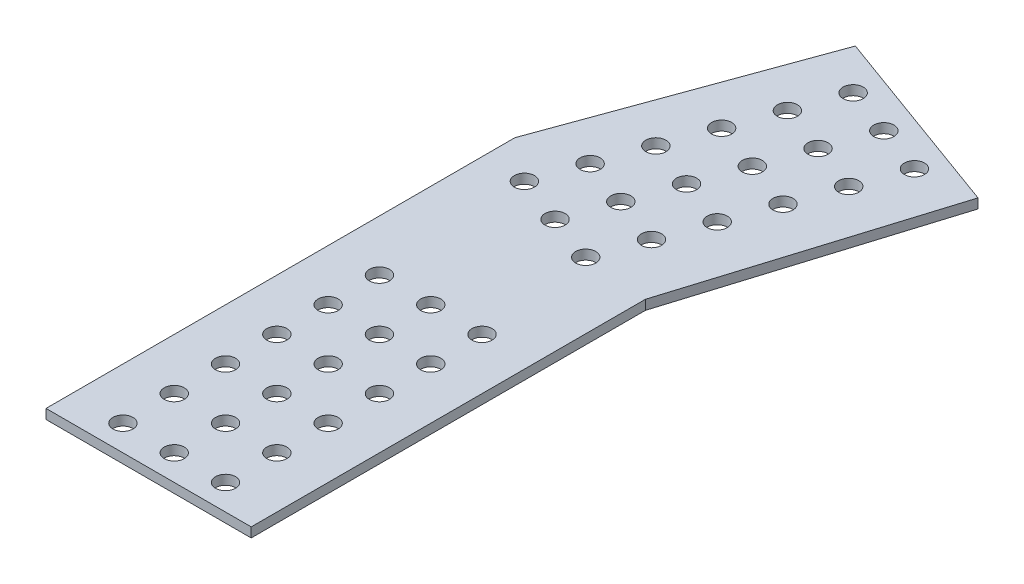
SolidWorks part; units mm, degrees
ref_plane "Front Plane" through (0, 0, 0) normal (0, 0, 1) x (1, 0, 0)
ref_plane "Top Plane" through (0, 0, 0) normal (0, 1, 0) x (1, 0, 0)
ref_plane "Right Plane" through (0, 0, 0) normal (1, 0, 0) x (0, 0, -1)
sketch "Sketch1" plane through (0, 0, 0) normal (0, 1, 0) x (1, 0, 0)
  line L0 (-80.3795, -295.1056) -> (-128.1159, -277.731) construction
  line L1 (-80.3795, -295.1056) -> (128.1159, 277.731) construction
  line L2 (-124.5455, -267.9214) -> (80.3795, 295.1056) construction
  line L3 (128.1159, 277.731) -> (80.3795, 295.1056) construction
  line L4 (-80.3795, -295.1056) -> (80.3795, 295.1056) construction
  line L5 (-128.1159, -277.731) -> (128.1159, 277.731) construction
  line L6 (104.2477, 286.4183) -> (-104.2477, -286.4183) construction
  line L7 (-73.7455, -307.8056) -> (-124.5455, -307.8056)
  line L8 (-73.7455, -307.8056) -> (-73.7455, -422.1056) construction
  line L9 (-73.7455, -422.1056) -> (-124.5455, -422.1056) construction
  line L10 (-124.5455, -307.8056) -> (-124.5455, -422.1056) construction
  line L11 (-99.1455, -307.8056) -> (-99.1455, -422.1056) construction
  line L12 (-105.4955, -307.8056) -> (-105.4955, -422.1056) construction
  line L13 (-99.1455, -307.8056) -> (-99.1455, -288.2754) construction
  line L14 (98.2807, 288.5901) -> (-110.2148, -284.2465) construction
  line L15 (-102.054, -206.1264) -> (-54.3176, -223.501)
  line L16 (-102.054, -206.1264) -> (-124.5455, -267.9214)
  line L19 (-73.7455, -384.0056) -> (-124.5455, -384.0056)
  line L20 (-73.7455, -307.8056) -> (-73.7455, -384.0056)
  line L21 (-124.5455, -307.8056) -> (-124.5455, -384.0056)
  line L22 (-124.5455, -307.8056) -> (-124.5455, -267.9214)
  line L23 (-124.5455, -267.9214) -> (-73.7455, -286.4111)
  line L24 (-73.7455, -307.8056) -> (-73.7455, -286.4111)
  line L25 (-73.7455, -286.4111) -> (-54.3176, -223.501)
  circle A0 centre (-111.8455, -314.1556) radius 2.4892
  circle A1 centre (-111.8455, -326.8556) radius 2.4892
  circle A2 centre (-111.8455, -339.5556) radius 2.4892
  circle A3 centre (-111.8455, -352.2556) radius 2.4892
  circle A4 centre (-111.8455, -364.9556) radius 2.4892
  circle A5 centre (-111.8455, -377.6556) radius 2.4892
  circle A6 centre (-111.8455, -390.3556) radius 2.4892 construction
  circle A7 centre (-111.8455, -403.0556) radius 2.4892 construction
  circle A8 centre (-111.8455, -415.7556) radius 2.4892 construction
  circle A9 centre (-99.1455, -403.0556) radius 2.4892 construction
  circle A10 centre (-99.1455, -390.3556) radius 2.4892 construction
  circle A11 centre (-99.1455, -377.6556) radius 2.4892
  circle A12 centre (-99.1455, -364.9556) radius 2.4892
  circle A13 centre (-99.1455, -352.2556) radius 2.4892
  circle A14 centre (-99.1455, -339.5556) radius 2.4892
  circle A15 centre (-99.1455, -326.8556) radius 2.4892
  circle A16 centre (-99.1455, -314.1556) radius 2.4892
  circle A17 centre (-86.4455, -415.7556) radius 2.4892 construction
  circle A18 centre (-86.4455, -403.0556) radius 2.4892 construction
  circle A19 centre (-86.4455, -390.3556) radius 2.4892 construction
  circle A20 centre (-86.4455, -377.6556) radius 2.4892
  circle A21 centre (-86.4455, -364.9556) radius 2.4892
  circle A22 centre (-86.4455, -352.2556) radius 2.4892
  circle A23 centre (-86.4455, -339.5556) radius 2.4892
  circle A24 centre (-86.4455, -326.8556) radius 2.4892
  circle A25 centre (-86.4455, -314.1556) radius 2.4892
  circle A26 centre (-99.1455, -415.7556) radius 2.4892 construction
  circle A27 centre (90.1418, 284.7949) radius 2.4892 construction
  circle A28 centre (85.7982, 272.8608) radius 2.4892 construction
  circle A29 centre (81.4545, 260.9267) radius 2.4892 construction
  circle A30 centre (77.1108, 248.9926) radius 2.4892 construction
  circle A31 centre (72.7672, 237.0585) radius 2.4892 construction
  circle A32 centre (68.4235, 225.1244) radius 2.4892 construction
  circle A33 centre (64.0799, 213.1903) radius 2.4892 construction
  circle A34 centre (59.7362, 201.2562) radius 2.4892 construction
  circle A35 centre (55.3926, 189.3221) radius 2.4892 construction
  circle A36 centre (51.0489, 177.3881) radius 2.4892 construction
  circle A37 centre (46.7053, 165.454) radius 2.4892 construction
  circle A38 centre (42.3616, 153.5199) radius 2.4892 construction
  circle A39 centre (38.0179, 141.5858) radius 2.4892 construction
  circle A40 centre (33.6743, 129.6517) radius 2.4892 construction
  circle A41 centre (29.3306, 117.7176) radius 2.4892 construction
  circle A42 centre (24.987, 105.7835) radius 2.4892 construction
  circle A43 centre (20.6433, 93.8494) radius 2.4892 construction
  circle A44 centre (16.2997, 81.9153) radius 2.4892 construction
  circle A45 centre (11.956, 69.9812) radius 2.4892 construction
  circle A46 centre (7.6124, 58.0471) radius 2.4892 construction
  circle A47 centre (3.2687, 46.113) radius 2.4892 construction
  circle A48 centre (-1.075, 34.1789) radius 2.4892 construction
  circle A49 centre (-5.4186, 22.2448) radius 2.4892 construction
  circle A50 centre (-9.7623, 10.3107) radius 2.4892 construction
  circle A51 centre (-14.1059, -1.6234) radius 2.4892 construction
  circle A52 centre (-18.4496, -13.5575) radius 2.4892 construction
  circle A53 centre (-22.7932, -25.4916) radius 2.4892 construction
  circle A54 centre (-27.1369, -37.4257) radius 2.4892 construction
  circle A55 centre (-31.4805, -49.3598) radius 2.4892 construction
  circle A56 centre (-35.8242, -61.2939) radius 2.4892 construction
  circle A57 centre (-40.1679, -73.228) radius 2.4892 construction
  circle A58 centre (-44.5115, -85.1621) radius 2.4892 construction
  circle A59 centre (-48.8552, -97.0962) radius 2.4892 construction
  circle A60 centre (-53.1988, -109.0303) radius 2.4892 construction
  circle A61 centre (-57.5425, -120.9644) radius 2.4892 construction
  circle A62 centre (-61.8861, -132.8985) radius 2.4892 construction
  circle A63 centre (-66.2298, -144.8325) radius 2.4892 construction
  circle A64 centre (-70.5734, -156.7666) radius 2.4892 construction
  circle A65 centre (-74.9171, -168.7007) radius 2.4892 construction
  circle A66 centre (-79.2608, -180.6348) radius 2.4892 construction
  circle A67 centre (-83.6044, -192.5689) radius 2.4892 construction
  circle A68 centre (-87.9481, -204.503) radius 2.4892 construction
  circle A69 centre (-92.2917, -216.4371) radius 2.4892
  circle A70 centre (-96.6354, -228.3712) radius 2.4892
  circle A71 centre (-100.979, -240.3053) radius 2.4892
  circle A72 centre (-105.3227, -252.2394) radius 2.4892
  circle A73 centre (-109.6664, -264.1735) radius 2.4892
  circle A74 centre (-114.01, -276.1076) radius 2.4892
  circle A75 centre (62.983, 173.0444) radius 2.4892 construction
  circle A76 centre (67.3267, 184.9785) radius 2.4892 construction
  circle A77 centre (71.6703, 196.9126) radius 2.4892 construction
  circle A78 centre (76.014, 208.8467) radius 2.4892 construction
  circle A79 centre (80.3576, 220.7808) radius 2.4892 construction
  circle A80 centre (84.7013, 232.7149) radius 2.4892 construction
  circle A81 centre (89.0449, 244.649) radius 2.4892 construction
  circle A82 centre (93.3886, 256.5831) radius 2.4892 construction
  circle A83 centre (97.7323, 268.5172) radius 2.4892 construction
  circle A84 centre (102.0759, 280.4513) radius 2.4892 construction
  circle A85 centre (-102.0759, -280.4513) radius 2.4892
  circle A86 centre (-97.7323, -268.5172) radius 2.4892
  circle A87 centre (-93.3886, -256.5831) radius 2.4892
  circle A88 centre (-89.0449, -244.649) radius 2.4892
  circle A89 centre (-84.7013, -232.7149) radius 2.4892
  circle A90 centre (-80.3576, -220.7808) radius 2.4892
  circle A91 centre (-76.014, -208.8467) radius 2.4892 construction
  circle A92 centre (-71.6703, -196.9126) radius 2.4892 construction
  circle A93 centre (-67.3267, -184.9785) radius 2.4892 construction
  circle A94 centre (-62.983, -173.0444) radius 2.4892 construction
  circle A95 centre (-58.6394, -161.1103) radius 2.4892 construction
  circle A96 centre (-54.2957, -149.1762) radius 2.4892 construction
  circle A97 centre (-49.952, -137.2421) radius 2.4892 construction
  circle A98 centre (-45.6084, -125.308) radius 2.4892 construction
  circle A99 centre (-41.2647, -113.3739) radius 2.4892 construction
  circle A100 centre (-36.9211, -101.4398) radius 2.4892 construction
  circle A101 centre (-32.5774, -89.5057) radius 2.4892 construction
  circle A102 centre (-28.2338, -77.5716) radius 2.4892 construction
  circle A103 centre (-23.8901, -65.6375) radius 2.4892 construction
  circle A104 centre (-19.5465, -53.7034) radius 2.4892 construction
  circle A105 centre (-15.2028, -41.7693) radius 2.4892 construction
  circle A106 centre (-10.8591, -29.8352) radius 2.4892 construction
  circle A107 centre (-6.5155, -17.9011) radius 2.4892 construction
  circle A108 centre (-2.1718, -5.967) radius 2.4892 construction
  circle A109 centre (2.1718, 5.967) radius 2.4892 construction
  circle A110 centre (6.5155, 17.9011) radius 2.4892 construction
  circle A111 centre (10.8591, 29.8352) radius 2.4892 construction
  circle A112 centre (15.2028, 41.7693) radius 2.4892 construction
  circle A113 centre (19.5465, 53.7034) radius 2.4892 construction
  circle A114 centre (23.8901, 65.6375) radius 2.4892 construction
  circle A115 centre (28.2338, 77.5716) radius 2.4892 construction
  circle A116 centre (32.5774, 89.5057) radius 2.4892 construction
  circle A117 centre (36.9211, 101.4398) radius 2.4892 construction
  circle A118 centre (41.2647, 113.3739) radius 2.4892 construction
  circle A119 centre (45.6084, 125.308) radius 2.4892 construction
  circle A120 centre (49.952, 137.2421) radius 2.4892 construction
  circle A121 centre (54.2957, 149.1762) radius 2.4892 construction
  circle A122 centre (58.6394, 161.1103) radius 2.4892 construction
  circle A123 centre (-90.1418, -284.7949) radius 2.4892
  circle A124 centre (-85.7982, -272.8608) radius 2.4892
  circle A125 centre (-81.4545, -260.9267) radius 2.4892
  circle A126 centre (-77.1108, -248.9926) radius 2.4892
  circle A127 centre (-72.7672, -237.0585) radius 2.4892
  circle A128 centre (-68.4235, -225.1244) radius 2.4892
  circle A129 centre (-64.0799, -213.1903) radius 2.4892 construction
  circle A130 centre (-59.7362, -201.2562) radius 2.4892 construction
  circle A131 centre (-55.3926, -189.3221) radius 2.4892 construction
  circle A132 centre (-51.0489, -177.3881) radius 2.4892 construction
  circle A133 centre (-46.7053, -165.454) radius 2.4892 construction
  circle A134 centre (-42.3616, -153.5199) radius 2.4892 construction
  circle A135 centre (-38.0179, -141.5858) radius 2.4892 construction
  circle A136 centre (-33.6743, -129.6517) radius 2.4892 construction
  circle A137 centre (-29.3306, -117.7176) radius 2.4892 construction
  circle A138 centre (-24.987, -105.7835) radius 2.4892 construction
  circle A139 centre (-20.6433, -93.8494) radius 2.4892 construction
  circle A140 centre (-16.2997, -81.9153) radius 2.4892 construction
  circle A141 centre (-11.956, -69.9812) radius 2.4892 construction
  circle A142 centre (-7.6124, -58.0471) radius 2.4892 construction
  circle A143 centre (-3.2687, -46.113) radius 2.4892 construction
  circle A144 centre (1.075, -34.1789) radius 2.4892 construction
  circle A145 centre (5.4186, -22.2448) radius 2.4892 construction
  circle A146 centre (9.7623, -10.3107) radius 2.4892 construction
  circle A147 centre (14.1059, 1.6234) radius 2.4892 construction
  circle A148 centre (18.4496, 13.5575) radius 2.4892 construction
  circle A149 centre (22.7932, 25.4916) radius 2.4892 construction
  circle A150 centre (27.1369, 37.4257) radius 2.4892 construction
  circle A151 centre (31.4805, 49.3598) radius 2.4892 construction
  circle A152 centre (35.8242, 61.2939) radius 2.4892 construction
  circle A153 centre (40.1679, 73.228) radius 2.4892 construction
  circle A154 centre (44.5115, 85.1621) radius 2.4892 construction
  circle A155 centre (48.8552, 97.0962) radius 2.4892 construction
  circle A156 centre (53.1988, 109.0303) radius 2.4892 construction
  circle A157 centre (57.5425, 120.9644) radius 2.4892 construction
  circle A158 centre (61.8861, 132.8985) radius 2.4892 construction
  circle A159 centre (66.2298, 144.8325) radius 2.4892 construction
  circle A160 centre (70.5734, 156.7666) radius 2.4892 construction
  circle A161 centre (74.9171, 168.7007) radius 2.4892 construction
  circle A162 centre (79.2608, 180.6348) radius 2.4892 construction
  circle A163 centre (83.6044, 192.5689) radius 2.4892 construction
  circle A164 centre (87.9481, 204.503) radius 2.4892 construction
  circle A165 centre (92.2917, 216.4371) radius 2.4892 construction
  circle A166 centre (96.6354, 228.3712) radius 2.4892 construction
  circle A167 centre (100.979, 240.3053) radius 2.4892 construction
  circle A168 centre (105.3227, 252.2394) radius 2.4892 construction
  circle A169 centre (109.6664, 264.1735) radius 2.4892 construction
  circle A170 centre (114.01, 276.1076) radius 2.4892 construction
  point P1 (0, 0)
  dimension "D9" = 4.9784
  dimension "D15" = 4.9784
  dimension "D1" = 50.8
  dimension "D2" = 609.6
  dimension "D3" = 50.8
  dimension "D4" = 114.3
  dimension "D5" = 20
  dimension "D6" = 12.7
  dimension "D7" = 30.2858
  dimension "D8" = 6.35
  dimension "D10" = 6.35
  dimension "D11" = 12.7
  dimension "D13" = 12.7
  dimension "D14" = 6.35
  dimension "D16" = 6.35
  dimension "D17" = 12.7
  dimension "D19" = 12.7
  dimension "D20" = 6.35
  dimension "D21" = 6.35
  dimension "D12" = 9
  dimension "D18" = 48
extrude "Boss-Extrude1" add sketch "Sketch1" along normal blind 2.3813 contours L7 L21 L19 L20 A24 A22 A20 A15 A13 A11 A5 A4 A3 A2 A1 A0 A12 A14 A16 A21 A23 A25 | L7 L24 L23 L22 A85 A74 A123 | L23 L25 L15 L16 A127 A125 A90 A88 A86 A73 A72 A71 A70 A69 A87 A89 A124 A126 A128
